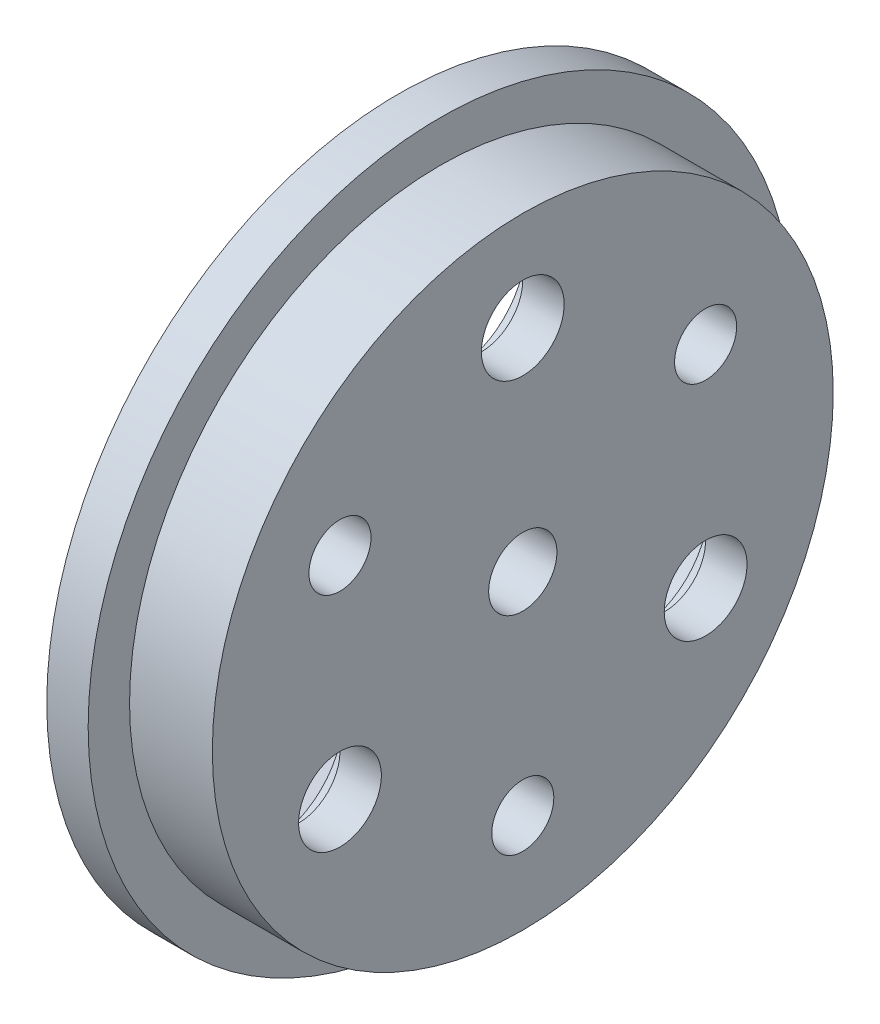
SolidWorks part; units mm, degrees
ref_plane "前视基准面" through (0, 0, 0) normal (0, 0, 1) x (1, 0, 0)
ref_plane "上视基准面" through (0, 0, 0) normal (0, 1, 0) x (1, 0, 0)
ref_plane "右视基准面" through (0, 0, 0) normal (1, 0, 0) x (0, 0, -1)
other "Configuration Table"
sketch "草图4" plane through (0, 0, 0) normal (1, 0, 0) x (0, 0, -1)
  circle A0 centre (0, 0) radius 17
extrude "凸台-拉伸2" add sketch "草图4" along normal blind 2
sketch "草图5" plane through (2, 0, 0) normal (1, 0, 0) x (0, 0, -1)
  circle A0 centre (0, 0) radius 15
extrude "凸台-拉伸3" add sketch "草图5" along normal blind 4
sketch "草图6" plane through (0, 0, 0) normal (-1, 0, 0) x (0, 0, 1)
  line L0 (0, 0) -> (0, 18) construction
  line L1 (0, 0) -> (15.5885, -9) construction
  line L2 (0, 0) -> (-15.5885, -9) construction
  line L3 (-3.0311, 12.75) -> (-12.5574, -3.75)
  line L4 (-9.5263, -9) -> (9.5263, -9)
  line L5 (12.5574, -3.75) -> (3.0311, 12.75)
  arc A0 (9.5263, -9) -> (12.5574, -3.75) centre (9.5263, -5.5) ccw
  arc A1 (-12.5574, -3.75) -> (-9.5263, -9) centre (-9.5263, -5.5) ccw
  arc A2 (-3.0311, 12.75) -> (3.0311, 12.75) centre (0, 11) cw
  point P7 (0, 0)
  dimension "D3" = 3.5
  dimension "D1" = 18
  dimension "D2" = 3
extrude "切除-拉伸1" cut sketch "草图6" against normal blind 2.6
sketch "草图7" plane through (2.6, 0, 0) normal (-1, 0, 0) x (0, 0, 1)
  line L0 (0, 0) -> (0, 10.2)
  line L1 (0, 0) -> (8.8335, -5.1)
  line L2 (0, 0) -> (-8.8335, -5.1)
  circle A0 centre (0, 10.2) radius 3.55
  circle A1 centre (8.8335, -5.1) radius 3.55
  circle A2 centre (-8.8335, -5.1) radius 3.55
  point P10 (0, 0)
  dimension "D1" = 7.1
  dimension "D2" = 3
extrude "切除-拉伸2" cut sketch "草图7" against normal blind 1.4
sketch "草图8" plane through (2.6, 0, 0) normal (-1, 0, 0) x (0, 0, 1)
  line L0 (0, 0) -> (0, 10.2)
  line L1 (0, 0) -> (8.8335, -5.1)
  line L2 (0, 0) -> (-8.8335, -5.1)
  circle A0 centre (0, 10.2) radius 2
  circle A1 centre (8.8335, -5.1) radius 2
  circle A2 centre (-8.8335, -5.1) radius 2
  point P11 (0, 0)
  dimension "D1" = 4
  dimension "D2" = 3
extrude "切除-拉伸3" cut sketch "草图8" against normal through all
sketch "草图9" plane through (2.6, 0, 0) normal (-1, 0, 0) x (0, 0, 1)
  circle A0 centre (0, 0) radius 5.5
  dimension "D1" = 11
extrude "切除-拉伸4" cut sketch "草图9" against normal blind 1
sketch "草图11" plane through (3.6, 0, 0) normal (-1, 0, 0) x (0, 0, 1)
  circle A0 centre (0, 0) radius 1.65
  dimension "D1" = 3.3
extrude "切除-拉伸5" cut sketch "草图11" against normal through all
sketch "草图13" plane through (6, 0, 0) normal (1, 0, 0) x (0, 0, -1)
  line L0 (0, 0) -> (0, 10.2)
  line L1 (0, 0) -> (-8.8335, 5.1)
  circle A1 centre (-8.8335, 5.1) radius 1.5
  circle A2 centre (8.8335, 5.1) radius 1.5
  circle A3 centre (0, -10.2) radius 1.5
  point P12 (0, 0)
  dimension "D3" = 3
  dimension "D1" = 10.2
  dimension "D2" = 60
extrude "切除-拉伸6" cut sketch "草图13" against normal through all
